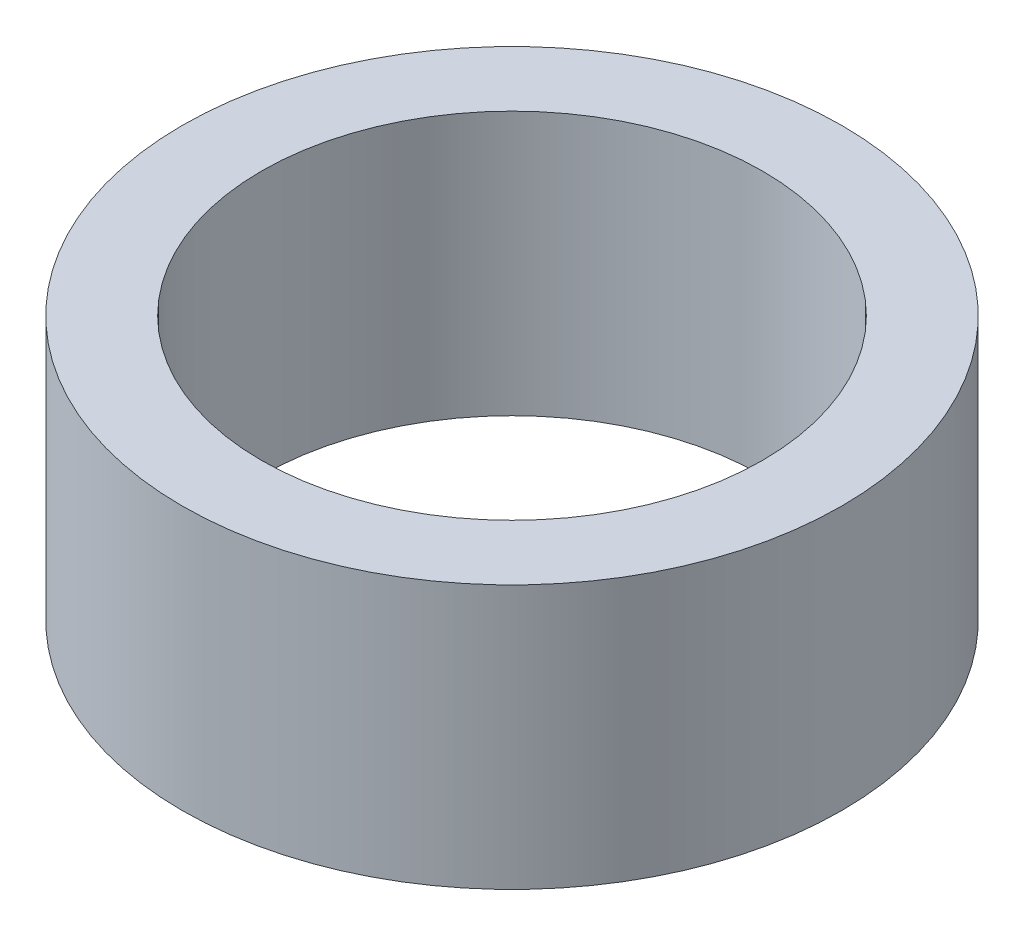
SolidWorks part; units mm, degrees
material "6061-T6 (SS)"
ref_plane "Front Plane" through (0, 0, 0) normal (0, 0, 1) x (1, 0, 0)
ref_plane "Top Plane" through (0, 0, 0) normal (0, 1, 0) x (1, 0, 0)
ref_plane "Right Plane" through (0, 0, 0) normal (1, 0, 0) x (0, 0, -1)
sketch "Sketch1" plane through (0, 0, 0) normal (0, 1, 0) x (1, 0, 0)
  circle A0 centre (0, 0) radius 6.25
  circle A1 centre (0, 0) radius 4.75
extrude "Boss-Extrude1" add sketch "Sketch1" along normal blind 5
